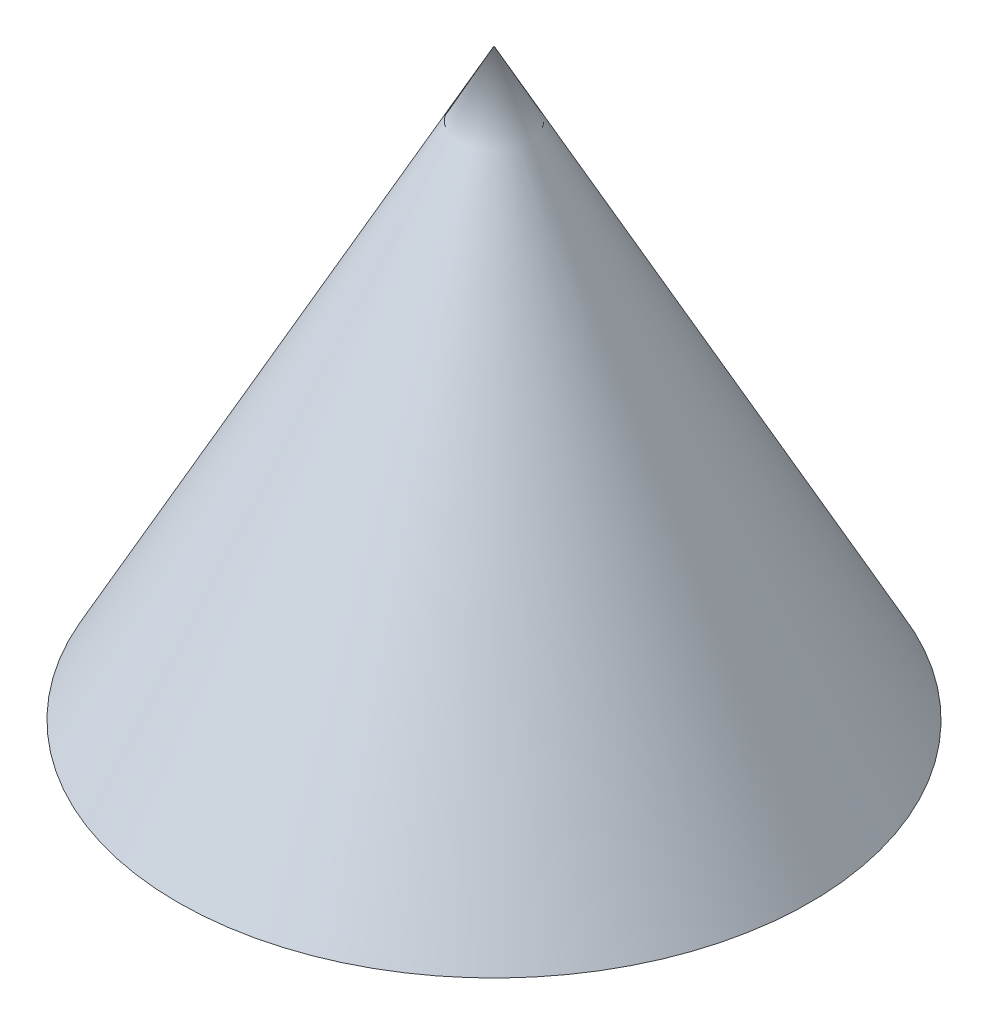
SolidWorks part; units mm, degrees
material "ABS"
ref_plane "正面" through (0, 0, 0) normal (0, 0, 1) x (1, 0, 0)
ref_plane "平面" through (0, 0, 0) normal (0, 1, 0) x (1, 0, 0)
ref_plane "右側面" through (0, 0, 0) normal (1, 0, 0) x (0, 0, -1)
sketch "ｽｹｯﾁ1" plane through (0, 0, 0) normal (0, 0, 1) x (1, 0, 0)
  line L0 (0, 0) -> (0, 6)
  line L1 (0, 6) -> (-3.25, 0)
  line L2 (-3.25, 0) -> (0, 0)
  dimension "D1" = 6
  dimension "D2" = 3.25
revolve "回転1" add sketch "ｽｹｯﾁ1" angle 360 about L0
sketch "ｽｹｯﾁ2" plane through (0, 0, 0) normal (0, -1, 0) x (1, 0, 0)
  circle A0 centre (0, 0) radius 0.9
  dimension "D1" = 1.8
extrude "ｶｯﾄ - 押し出し1" cut sketch "ｽｹｯﾁ2" against normal blind 3
